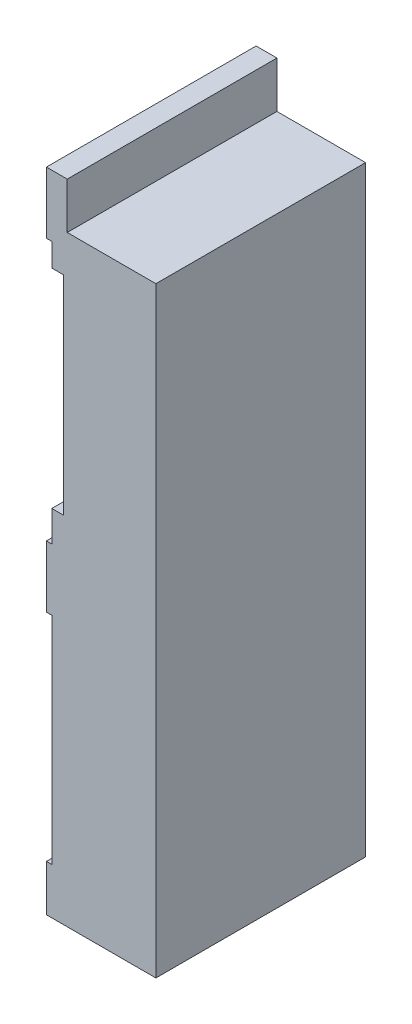
SolidWorks part; units mm, degrees
ref_plane "前视基准面" through (0, 0, 0) normal (0, 0, 1) x (1, 0, 0)
ref_plane "上视基准面" through (0, 0, 0) normal (0, 1, 0) x (1, 0, 0)
ref_plane "右视基准面" through (0, 0, 0) normal (1, 0, 0) x (0, 0, -1)
other "Configuration Table"
sketch "草图1" plane through (0, 0, 0) normal (0, 0, 1) x (1, 0, 0)
  line L0 (10.2, 0) -> (16.95, 0)
  line L1 (16.95, 0) -> (16.95, 54)
  line L2 (16.95, 54) -> (11.2, 54)
  line L3 (11.2, 54) -> (11.2, 57)
  line L4 (11.2, 57) -> (4.7, 57)
  line L5 (4.7, 57) -> (4.7, 53)
  line L6 (4.7, 53) -> (10.2, 53)
  line L7 (10.2, 53) -> (10.2, 51.5)
  line L8 (10.2, 51.5) -> (10.95, 51.5)
  line L9 (10.95, 51.5) -> (10.95, 38)
  line L10 (10.95, 38) -> (10.2, 38)
  line L11 (10.2, 38) -> (10.2, 36)
  line L12 (10.2, 36) -> (4.7, 36)
  line L13 (4.7, 36) -> (4.7, 32)
  line L14 (4.7, 32) -> (10.2, 32)
  line L15 (10.2, 32) -> (10.2, 0)
  dimension "x0" = 10.2
  dimension "x1" = 16.95
  dimension "x3" = 11.2
  dimension "x5" = 4.7
  dimension "x7" = 10.2
  dimension "x9" = 10.95
  dimension "x11" = 10.2
  dimension "x13" = 4.7
  dimension "y2" = 54
  dimension "y4" = 57
  dimension "y6" = 53
  dimension "y8" = 51.5
  dimension "y10" = 38
  dimension "y12" = 36
  dimension "y14" = 32
extrude "Guide_and_solid_stops" add sketch "草图1" along normal blind 13.6
ref_plane "Channel_midplane" through (0, 0, 6.8) normal (0, 0, 1) x (1, 0, 0)
sketch "草图3" plane through (0, 0, 6.8) normal (0, 0, 1) x (1, 0, 0)
  line L0 (7, 37.5) -> (15.4, 37.5)
  line L1 (15.4, 37.5) -> (15.4, 51.5)
  line L2 (15.4, 51.5) -> (7, 51.5)
  line L3 (7, 51.5) -> (7, 37.5)
  dimension "x0" = 7
  dimension "x1" = 15.4
  dimension "y0" = 37.5
  dimension "y2" = 51.5
extrude "Nut_tongue_channel" cut sketch "草图3" against normal mid plane 5.6
sketch "草图4" plane through (0, 0, 6.8) normal (0, 0, 1) x (1, 0, 0)
  line L0 (4, 31) -> (10.25, 31)
  line L1 (10.25, 31) -> (10.25, 36.2)
  line L2 (10.25, 36.2) -> (4, 36.2)
  line L3 (4, 36.2) -> (4, 31)
  dimension "x0" = 4
  dimension "x1" = 10.25
  dimension "y0" = 31
  dimension "y2" = 36.2
extrude "Lower_yoke_relief" cut sketch "草图4" against normal mid plane 6
sketch "草图5" plane through (0, 0, 0) normal (0, 0, 1) x (1, 0, 0)
  line L0 (7.5, 15) -> (11.2, 15)
  line L1 (11.2, 15) -> (11.2, 18)
  line L2 (11.2, 18) -> (7.5, 18)
  line L3 (7.5, 18) -> (7.5, 15)
  dimension "x0" = 7.5
  dimension "x1" = 11.2
  dimension "y0" = 15
  dimension "y2" = 18
extrude "Lower_inward_stop" add sketch "草图5" along normal blind 3.8
ref_plane "Lower_stop_rear_plane" through (0, 0, 9.8) normal (0, 0, 1) x (1, 0, 0)
sketch "草图7" plane through (0, 0, 9.8) normal (0, 0, 1) x (1, 0, 0)
  line L0 (7.5, 15) -> (11.2, 15)
  line L1 (11.2, 15) -> (11.2, 18)
  line L2 (11.2, 18) -> (7.5, 18)
  line L3 (7.5, 18) -> (7.5, 15)
  dimension "x0" = 7.5
  dimension "x1" = 11.2
  dimension "y0" = 15
  dimension "y2" = 18
extrude "凸台-拉伸2" add sketch "草图7" along normal blind 3.8
sketch "草图8" plane through (0, 0, 0) normal (0, 0, 1) x (1, 0, 0)
  line L0 (3, -2) -> (20, -2)
  line L1 (20, -2) -> (20, 15)
  line L2 (20, 15) -> (3, 15)
  line L3 (3, 15) -> (3, -2)
  dimension "x0" = 3
  dimension "x1" = 20
  dimension "y0" = 2
  dimension "y2" = 15
extrude "Remove_lower_tail" cut sketch "草图8" against normal through all and the other way through all
sketch "草图9" plane through (0, 0, 0) normal (0, 0, 1) x (1, 0, 0)
  line L0 (0, 13) -> (9.85, 13)
  line L1 (9.85, 13) -> (9.85, 59)
  line L2 (9.85, 59) -> (0, 59)
  line L3 (0, 59) -> (0, 13)
  dimension "x1" = 9.85
  dimension "y0" = 13
  dimension "y2" = 59
extrude "Wider_shaft_relief" cut sketch "草图9" against normal through all and the other way through all
